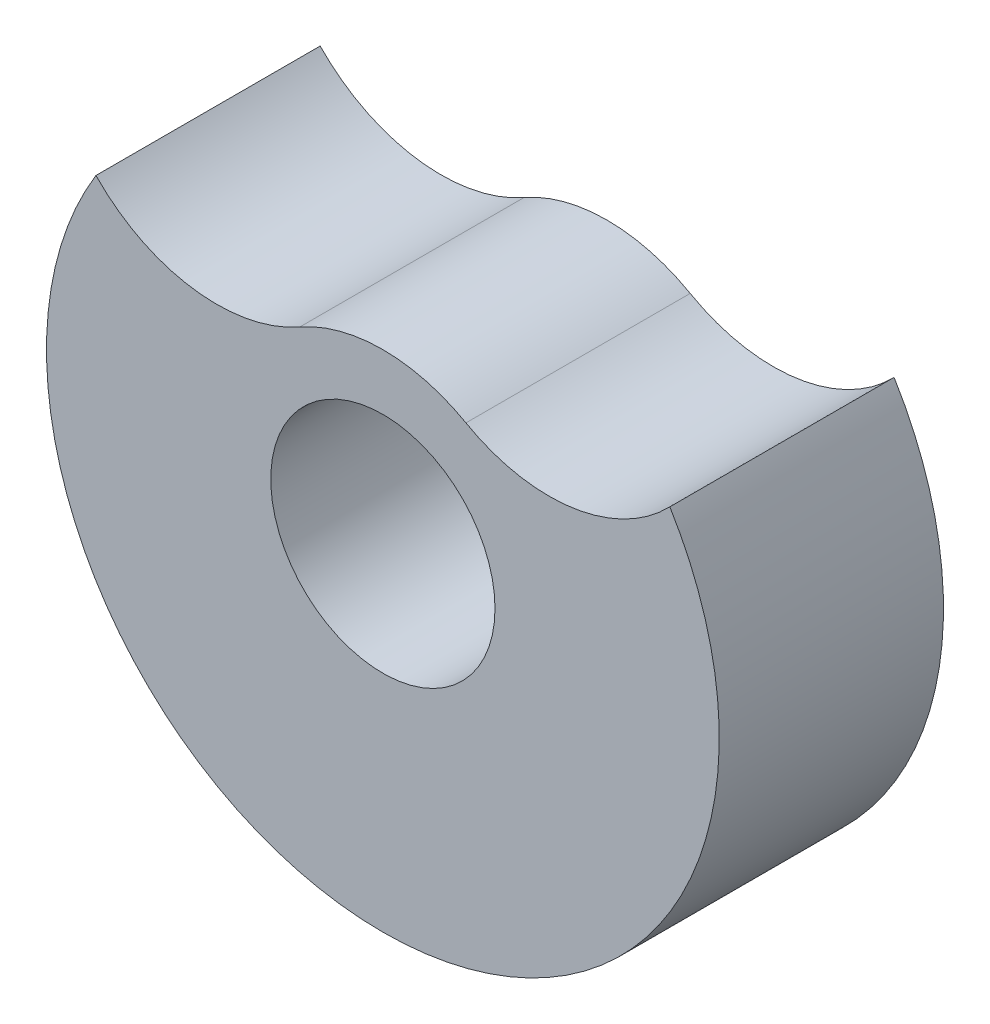
SolidWorks part; units mm, degrees
ref_plane "Front Plane" through (0, 0, 0) normal (0, 0, 1) x (1, 0, 0)
ref_plane "Top Plane" through (0, 0, 0) normal (0, 1, 0) x (1, 0, 0)
ref_plane "Right Plane" through (0, 0, 0) normal (1, 0, 0) x (0, 0, -1)
sketch "Sketch2" plane through (0, 0, 0) normal (0, 0, 1) x (1, 0, 0)
  circle A0 centre (0, 0) radius 15
  dimension "D1" = 30
extrude "Boss-Extrude1" add sketch "Sketch2" along normal blind 10
sketch "Sketch3" plane through (0, 0, 10) normal (0, 0, 1) x (1, 0, 0)
  circle A0 centre (0, 0) radius 5
  dimension "D1" = 10
extrude "Cut-Extrude1" cut sketch "Sketch3" against normal up to next
sketch "Sketch7" plane through (0, 0, 10) normal (0, 0, 1) x (1, 0, 0)
  arc A0 (3.7041, 6.5215) -> (-3.7041, 6.5215) centre (0, 0) ccw
  arc A1 (0, 14.2124) -> (-3.7041, 6.5215) centre (-7.4083, 13.0429) ccw
  circle A2 centre (0, 0) radius 15 construction
  arc A3 (3.7041, 6.5215) -> (0, 14.2124) centre (7.4083, 13.0429) ccw
  point P7 (-12.7966, 7.826)
  point P8 (4.9091, -14.174)
  dimension "D1" = 15
  dimension "D2" = 22
  dimension "D3" = 14.8165
extrude "Cut-Extrude2" cut sketch "Sketch7" against normal through all
